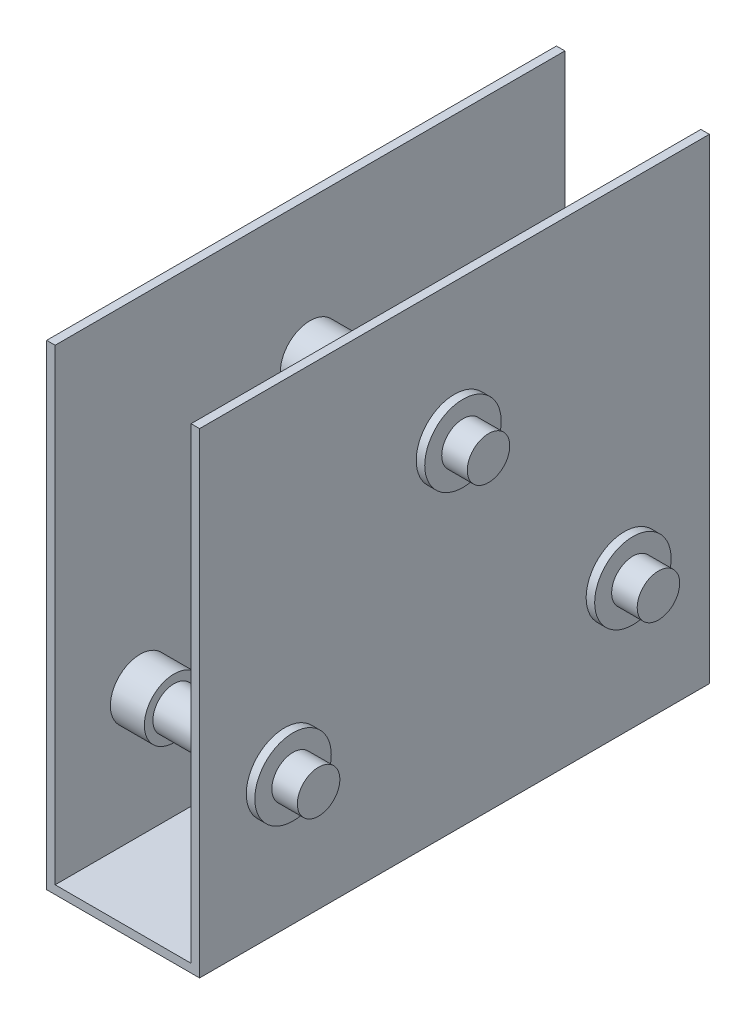
SolidWorks part; units mm, degrees
ref_plane "Front Plane" through (0, 0, 0) normal (0, 0, 1) x (1, 0, 0)
ref_plane "Top Plane" through (0, 0, 0) normal (0, 1, 0) x (1, 0, 0)
ref_plane "Right Plane" through (0, 0, 0) normal (1, 0, 0) x (0, 0, -1)
sketch "Sketch1" plane through (0, 0, 0) normal (0, 0, 1) x (1, 0, 0)
  line L0 (-14.2875, 88.9) -> (-14.2875, 0)
  line L1 (-14.2875, 0) -> (14.2875, 0)
  line L2 (14.2875, 0) -> (14.2875, 88.9)
  line L3 (14.2875, 88.9) -> (12.7, 88.9)
  line L4 (12.7, 88.9) -> (12.7, 1.5875)
  line L5 (12.7, 1.5875) -> (-12.7, 1.5875)
  line L6 (-12.7, 1.5875) -> (-12.7, 88.9)
  line L7 (-12.7, 88.9) -> (-14.2875, 88.9)
  dimension "D1" = 1.5875
  dimension "D2" = 1.5875
  dimension "D3" = 88.9
  dimension "D4" = 28.575
extrude "Boss-Extrude1" add sketch "Sketch1" along normal blind 95.25
sketch "Sketch3" plane through (14.2875, 0, 0) normal (1, 0, 0) x (0, 0, -1)
  line L0 (-79.375, 25.4) -> (-15.875, 25.4) construction
  line L1 (-47.625, 25.4) -> (-47.625, 63.5) construction
  line L2 (-79.375, 25.4) -> (-95.25, 25.4) construction
  line L3 (-95.25, 0) -> (-95.25, 88.9) construction
  line L4 (-15.875, 25.4) -> (0, 25.4) construction
  line L5 (0, 0) -> (0, 88.9) construction
  line L6 (-95.25, 0) -> (0, 0) construction
  circle A0 centre (-47.625, 63.5) radius 5.5562
  circle A1 centre (-79.375, 25.4) radius 5.5563
  circle A2 centre (-15.875, 25.4) radius 5.5562
  dimension "D1" = 11.1125
  dimension "D2" = 63.5
  dimension "D3" = 38.1
  dimension "D4" = 25.4
extrude "Boss-Extrude2" add sketch "Sketch3" along normal blind 1.5875 and the other way blind 30.1625
sketch "Sketch4" plane through (14.2875, 0, 0) normal (1, 0, 0) x (0, 0, -1)
  circle A0 centre (-47.625, 63.5) radius 7.1437
  circle A1 centre (-15.875, 25.4) radius 7.1438
  circle A2 centre (-79.375, 25.4) radius 7.1438
  dimension "D1" = 14.2875
extrude "Boss-Extrude3" add sketch "Sketch4" along normal up to surface (1.5875 mm away) up to face at (15.875, 69.0563, 47.625)
sketch "Sketch5" plane through (-14.2875, 0, 0) normal (-1, 0, 0) x (0, 0, 1)
  circle A0 centre (47.625, 63.5) radius 7.1437
  circle A1 centre (79.375, 25.4) radius 7.1438
  circle A2 centre (15.875, 25.4) radius 7.1438
  dimension "D1" = 14.2875
extrude "Boss-Extrude4" add sketch "Sketch5" along normal up to surface (1.5875 mm away) up to face at (-15.875, 69.0563, 47.625)
sketch "Sketch7" plane through (0, 1.5875, 0) normal (0, 1, 0) x (1, 0, 0)
  line L0 (12.7, 0) -> (-12.7, 0) construction
  line L1 (-6.35, 0) -> (6.35, 0)
  line L2 (-6.35, 0) -> (-6.35, -95.25)
  line L3 (-6.35, -95.25) -> (6.35, -95.25)
  line L4 (6.35, 0) -> (6.35, -95.25)
  line L5 (12.7, -95.25) -> (-12.7, -95.25) construction
  line L6 (-6.35, 0) -> (-12.7, 0) construction
  line L7 (6.35, 0) -> (12.7, 0) construction
  dimension "D1" = 12.7
extrude "Cut-Extrude1" cut sketch "Sketch7" along normal through all
sketch "Sketch6" plane through (-14.2875, 0, 0) normal (-1, 0, 0) x (0, 0, 1)
  circle A0 centre (47.625, 63.5) radius 3.9687
  circle A1 centre (79.375, 25.4) radius 3.9687
  circle A2 centre (15.875, 25.4) radius 3.9688
  dimension "D1" = 7.9375
extrude "Boss-Extrude5" add sketch "Sketch6" along normal blind 6.35 and the other way blind 34.9377
